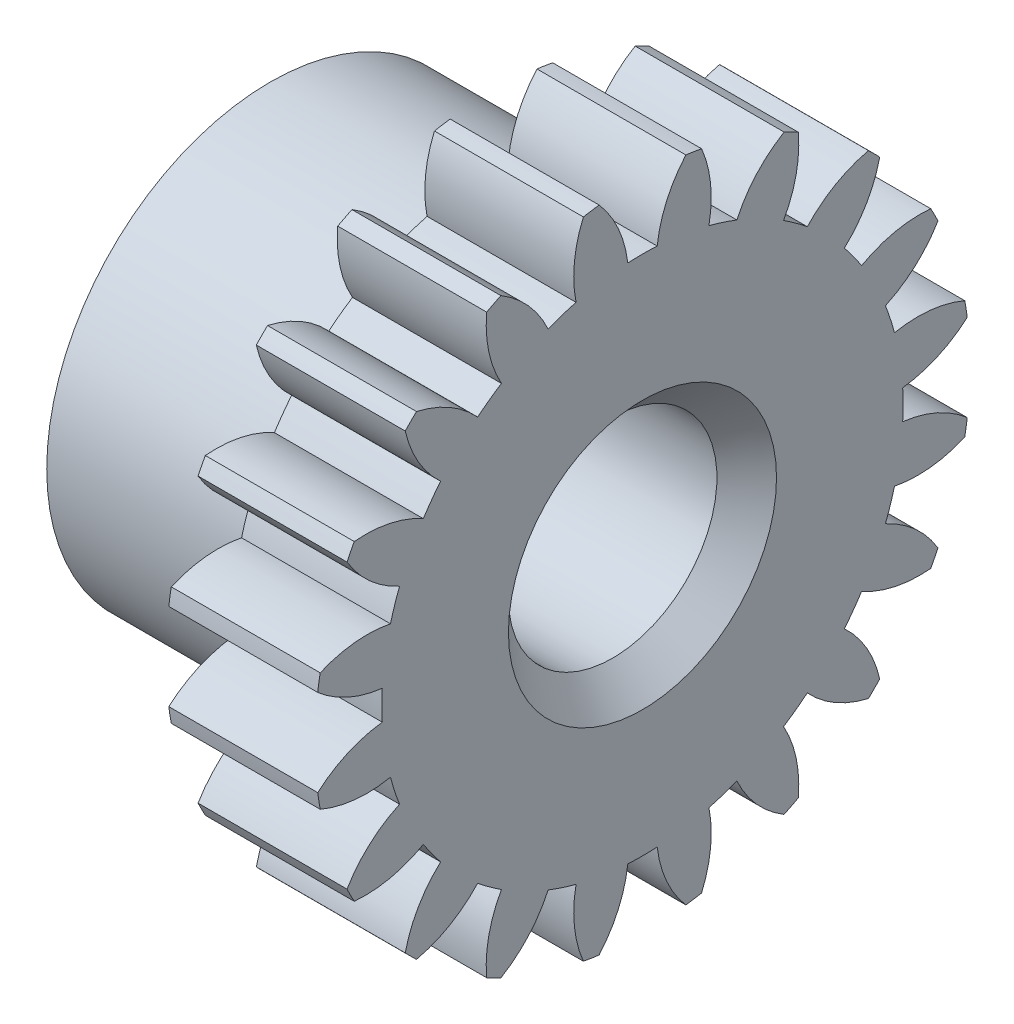
SolidWorks part; units mm, degrees
ref_plane "Plane1" through (0, 0, 0) normal (0, 0, 1) x (1, 0, 0)
ref_plane "Plane2" through (0, 0, 0) normal (0, 1, 0) x (1, 0, 0)
ref_plane "Plane3" through (0, 0, 0) normal (1, 0, 0) x (0, 0, -1)
sketch "HoldingSke" plane through (0, 0, 0) normal (0, 1, 0) x (1, 0, 0)
  line L0 (0, 0) -> (0.4698, -0.171)
  line L1 (-15, 0) -> (100, 0) construction
  line L2 (0, 0) -> (-2.1039, 2.3779)
  line L3 (0, 0) -> (-11.863, 4.5341)
  line L4 (0, 0) -> (8.1152, 2.9537)
  line L5 (0, 0) -> (-23.4238, -8.7364)
  line L6 (0, 0) -> (-8.2896, -5.593)
  line L7 (-2.1039, 2.3779) -> (3.2774, 26.7919)
  line L8 (-76.2, 54.61) -> (-73.9, 54.61)
  line L9 (-71.009, 38.7566) -> (-53.1078, 45.2721)
  line L10 (-76.2, 71.12) -> (104.1128, 71.12)
  line L11 (0, 0) -> (-10, 0)
  line L12 (-76.2, 101.6) -> (-76.133, 101.6)
  line L13 (24.9733, 27.94) -> (52.9518, 28.4284)
  line L14 (24.9733, 27.94) -> (24.9743, 27.94)
  line L15 (24.9733, 27.94) -> (100.4006, 29.5858)
  line L16 (-63.627, -2) -> (-12.827, -2)
  circle A0 centre (0, 0) radius 7
  circle A1 centre (0, 0) radius 15
  circle A2 centre (0, 0) radius 15
  circle A3 centre (0, 0) radius 7
  dimension "MHD" = 30
  dimension "Hub_dia" = 30
  dimension "Bore" = 14
  dimension "MBD" = 14
  dimension "Num_teeth" = 20
  dimension "Pitch" = 0.5
  dimension "Overall_len" = 25
  dimension "Show_teeth" = 20
  dimension "Thickness" = 10
  dimension "OAL" = 25.0001
  dimension "T_dim" = 2.3
  dimension "Ap" = 20
  dimension "H" = 19.05
  dimension "Pitch_radius" = 180.3128
  dimension "Width" = 10
  dimension "Backlash" = 0.067
  dimension "Addendum_fac" = 1
  dimension "Dedendum_fac" = 1.25
  dimension "Clearance_fac" = 0.25
  dimension "Dedendum_add" = 0.001
  dimension "Module" = 2
sketch "BasProSke" plane through (0, 0, 0) normal (0, 1, 0) x (1, 0, 0)
  line L0 (-10, 0) -> (60, 0) construction
  line L1 (0, 0) -> (0, 22)
  line L2 (0, 0) -> (10, 0)
  line L3 (10, 0) -> (10, 22)
  line L4 (10, 22) -> (0, 22)
  dimension "Thickness" = 10
  dimension "Diameter" = 44
revolve "Base-Revolve" add sketch "BasProSke" angle 360 about L0
sketch "TooCutSke" plane through (0, 0, 0) normal (1, 0, 0) x (0, 0, -1)
  line L1 (0, 0) -> (0, 107) construction
  line L2 (0, 0) -> (-1.6864, 19.9288) construction
  line L3 (0, 0) -> (-6.2409, 39.4033) construction
  line L4 (-1.6864, 19.9288) -> (-3.1204, 19.7016) construction
  arc A0 (0.9862, 17.4712) -> (-0.9862, 17.4712) centre (0, 0) ccw
  arc A1 (2.9329, 21.8293) -> (-2.9329, 21.8293) centre (0, 0) ccw
  circle A2 centre (0, 0) radius 20 construction
  circle A3 centre (0, 0) radius 18.7939 construction
  arc A4 (-0.9862, 17.4712) -> (-2.9329, 21.8293) centre (-8.9313, 16.536) ccw
  arc A5 (2.9329, 21.8293) -> (0.9862, 17.4712) centre (8.9313, 16.536) ccw
  dimension "Root_dia" = 34.998
  dimension "Overcut_dia" = 44.0508
  dimension "Pitch_dia" = 40
  dimension "Base_dia" = 37.5877
  dimension "Flank_rad" = 8
  dimension "Half_ang" = 9
  dimension "Half_CT" = 1.4519
extrude "ToothCut" cut sketch "TooCutSke" along normal through all
fillet "Breaks" [suppressed] radius 0.04
fillet "RootFillets" [suppressed] radius 0.501
pattern_circular "TeethCuts" count 20 every 18 about axis through (-10, 0, 0) along (1, 0, 0) of "ToothCut", "RootFillets", "Breaks"
sketch "HubNeaOneSke" plane through (0, 0, 0) normal (-1, 0, 0) x (0, 0, 1)
  circle A0 centre (0, 0) radius 15
  dimension "Diameter" = 30
extrude "HubNearOne" add sketch "HubNeaOneSke" along normal blind 15.0001
sketch "HubNeaBotSke" plane through (0, 0, 0) normal (-1, 0, 0) x (0, 0, 1)
  circle A0 centre (0, 0) radius 15
  dimension "Diameter" = 30
extrude "HubNearBoth" [suppressed] add sketch "HubNeaBotSke" along normal blind 7.5
ref_plane "FarPln" through (10, 0, 0) normal (1, 0, 0) x (0, 0, -1)
sketch "HubFarSke" plane through (10, 0, 0) normal (1, 0, 0) x (0, 0, -1)
  circle A0 centre (0, 0) radius 15
  dimension "Diameter" = 30
extrude "HubFar" [suppressed] add sketch "HubFarSke" along normal blind 7.5
sketch "BorSke" plane through (0, 0, 0) normal (1, 0, 0) x (0, 0, -1)
  circle A0 centre (0, 0) radius 7
  dimension "Diameter" = 14
extrude "Bore" cut sketch "BorSke" along normal mid plane 50.0001
sketch "KeySke" plane through (0, 0, 0) normal (1, 0, 0) x (0, 0, -1)
  line L0 (-2.5, 0) -> (-2.5, 9.3)
  line L1 (-2.5, 9.3) -> (2.5, 9.3)
  line L2 (2.5, 9.3) -> (2.5, 0)
  line L3 (0, 0) -> (0, 34) construction
  line L4 (-2.5, 0) -> (2.5, 0)
  dimension "Offset" = 9.3
  dimension "Width" = 5
extrude "Keyway" [suppressed] cut sketch "KeySke" along normal mid plane 50.0001
pattern_circular "Keyway2" [suppressed] count 2 every 90 about axis through (-10, 0, 0) along (1, 0, 0)
chamfer "倒角1" distance 2 angle 45 2 edges at (10, 0, 7) (-15.0001, 0, 7)
equation "' \"Module@HoldingSke\" = 6.35"
equation "' \"Num_teeth@HoldingSke\" = 12"
equation "' \"Ap@HoldingSke\" =  20"
equation "' \"Ap@HoldingSke\" = 20"
equation "' \"Width@HoldingSke\" = 0.5 * 25.4"
equation "' \"Hub_dia@HoldingSke\"= 1 * 25.4"
equation "' \"Hub_dia@HoldingSke\" = 1 * 25.4"
equation "' \"Overall_len@HoldingSke\" = 1.0 * 25.4"
equation "' \"Bore@HoldingSke\" = 0.75 * 25.4"
equation "' \"T_dim@HoldingSke\" = 0.1 * 25.4"
equation "' \"Width@KeySke\" = 0.25 * 25.4"
equation "' \"Show_teeth@HoldingSke\" = 13"
equation "' \"Backlash@HoldingSke\" = 0.009 * 25.4"
equation "' \"Addendum_fac@HoldingSke\" = 1.0"
equation "' \"Dedendum_fac@HoldingSke\" = 1.25"
equation "' \"Dedendum_add@HoldingSke\" = 0.00005 * 25.4"
equation "' \"Clearance_fac@HoldingSke\" = 0.25"
equation "\"Pitch@HoldingSke\" = 1 / \"Module@HoldingSke\""
equation "\"Overcut_dia@TooCutSke\" = (\"Num_teeth@HoldingSke\" + 2 * \"Addendum_fac@HoldingSke\") / \"Pitch@HoldingSke\" + 0.002 * 25.4"
equation "\"Pitch_dia@TooCutSke\" = \"Num_teeth@HoldingSke\" / \"Pitch@HoldingSke\""
equation "\"Base_dia@TooCutSke\" = \"Num_teeth@HoldingSke\" / \"Pitch@HoldingSke\" * cos((\"Ap@HoldingSke\"  * 3.14159265 / 180))"
equation "\"Root_dia@TooCutSke\" = (\"Num_teeth@HoldingSke\" + 2) / \"Pitch@HoldingSke\" - 2 * (\"Addendum_fac@HoldingSke\" + \"Dedendum_fac@HoldingSke\") / \"Pitch@HoldingSke\" - \"Dedendum_add@HoldingSke\" * 2"
equation "\"Half_ang@TooCutSke\" = 180 / \"Num_teeth@HoldingSke\""
equation "\"Half_CT@TooCutSke\" = \"Num_teeth@HoldingSke\" / \"Pitch@HoldingSke\" * sin((3.14159265 / 2 / \"Num_teeth@HoldingSke\")) / 2 - 7 * \"Backlash@HoldingSke\" / 4"
equation "\"Flank_rad@TooCutSke\" = \"Num_teeth@HoldingSke\" / \"Pitch@HoldingSke\" / 5"
equation "\"Radius@RootFillets\" = \"Clearance_fac@HoldingSke\" / \"Pitch@HoldingSke\" + \"Dedendum_add@HoldingSke\""
equation "\"Break_rad@Breaks\" = 0.02 / \"Pitch@HoldingSke\""
equation "\"Thickness@HoldingSke\" = \"Width@HoldingSke\""
equation "\"OAL@HoldingSke\" = \"Thickness@HoldingSke\""
equation "\"MHD@HoldingSke\" = (\"Num_teeth@HoldingSke\" + 2) / \"Pitch@HoldingSke\" - 2 * (\"Addendum_fac@HoldingSke\" + \"Dedendum_fac@HoldingSke\")  / \"Pitch@HoldingSke\" - \"Dedendum_add@HoldingSke\" * 2"
equation "\"MBD@HoldingSke\" = (\"Num_teeth@HoldingSke\" + 2) / \"Pitch@HoldingSke\" - 2 * (\"Addendum_fac@HoldingSke\" + \"Dedendum_fac@HoldingSke\")  / \"Pitch@HoldingSke\" - \"Dedendum_add@HoldingSke\" * 2 - 0.002 * 25.4"
equation "\"MHD@HoldingSke\" = ((sgn( \"MHD@HoldingSke\" - \"Hub_dia@HoldingSke\" )-1)*( \"MHD@HoldingSke\" - \"Hub_dia@HoldingSke\" ))/-2+ \"Hub_dia@HoldingSke\""
equation "\"MBD@HoldingSke\" = ((sgn( \"MBD@HoldingSke\" - \"Bore@HoldingSke\" )-1)*( \"MBD@HoldingSke\" - \"Bore@HoldingSke\" ))/-2+ \"Bore@HoldingSke\""
equation "\"OAL@HoldingSke\" = ((sgn( \"OAL@HoldingSke\" - \"Overall_len@HoldingSke\" )+1)*( \"OAL@HoldingSke\" - \"Overall_len@HoldingSke\" ))/2 + \"Overall_len@HoldingSke\" + 0.000002 * 25.4"
equation "\"Num_teeth@TeethCuts\" = int( \"Show_teeth@HoldingSke\" ) + 1"
equation "\"Num_teeth@TeethCuts\" = ((sgn( \"Num_teeth@TeethCuts\" - \"Num_teeth@HoldingSke\" )-1)*( \"Num_teeth@TeethCuts\" - \"Num_teeth@HoldingSke\" ))/-2+ \"Num_teeth@HoldingSke\""
equation "\"Num_teeth@TeethCuts\" = ((sgn( \"Num_teeth@TeethCuts\" - 2.0)+1)*( \"Num_teeth@TeethCuts\" - 2.0))/2 +2.0"
equation "\"Angle@TeethCuts\" = 360.0 / \"Num_teeth@HoldingSke\""
equation "\"Diameter@BasProSke\" = (\"Num_teeth@HoldingSke\" + 2 * \"Addendum_fac@HoldingSke\") / \"Pitch@HoldingSke\""
equation "\"Thickness@BasProSke\"  = \"Thickness@HoldingSke\""
equation "' \"Fillet_rad@BasProSke\" =  \"Thickness@HoldingSke\" * 0.05"
equation "' \"Fillet_rad@BasProSke\" = \"Thickness@HoldingSke\" * 0.05"
equation "\"MHD@HoldingSke\" = ((sgn( \"MHD@HoldingSke\" - \"Root_dia@TooCutSke\" )-1)*( \"MHD@HoldingSke\" - \"Root_dia@TooCutSke\" ))/-2+ \"Root_dia@TooCutSke\""
equation "\"Diameter@HubNeaOneSke\" = \"MHD@HoldingSke\""
equation "\"Length@HubNearOne\" = \"OAL@HoldingSke\" - \"Thickness@BasProSke\""
equation "\"Diameter@HubNeaBotSke\" = \"MHD@HoldingSke\""
equation "\"Length@HubNearBoth\" = ( \"OAL@HoldingSke\" - \"Thickness@BasProSke\" ) / 2.0"
equation "\"Thickness@FarPln\" = \"Thickness@BasProSke\""
equation "\"Diameter@HubFarSke\" = \"MHD@HoldingSke\""
equation "\"Length@HubFar\" = ( \"OAL@HoldingSke\" - \"Thickness@BasProSke\" ) / 2.0"
equation "\"Diameter@BorSke\" = \"MBD@HoldingSke\""
equation "\"D1@Bore\" = \"OAL@HoldingSke\" * 2.0"
equation "\"D1@Keyway\" = \"OAL@HoldingSke\" * 2.0"
equation "\"Offset@KeySke\" = \"T_dim@HoldingSke\" + \"MBD@HoldingSke\" / 2.0"
